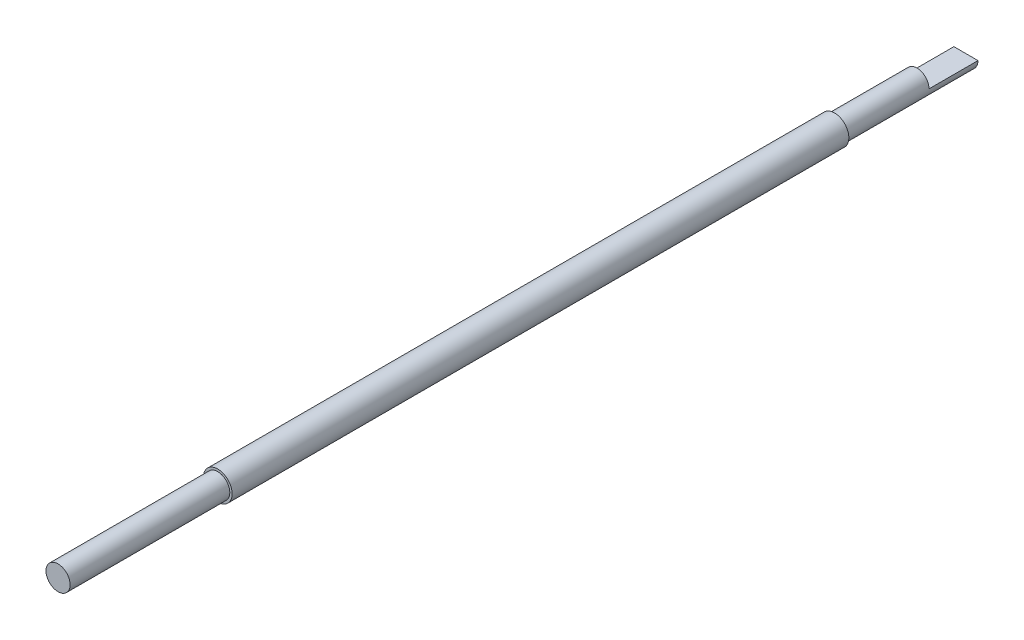
SolidWorks part; units mm, degrees
ref_plane "Front Plane" through (0, 0, 0) normal (0, 0, 1) x (1, 0, 0)
ref_plane "Top Plane" through (0, 0, 0) normal (0, 1, 0) x (1, 0, 0)
ref_plane "Right Plane" through (0, 0, 0) normal (1, 0, 0) x (0, 0, -1)
sketch "Sketch1" plane through (0, 0, 0) normal (0, 0, 1) x (1, 0, 0)
  circle A0 centre (0, 0) radius 4.7625
  dimension "D1" = 9.525
extrude "Boss-Extrude1" add sketch "Sketch1" along normal blind 301.26
sketch "Sketch3" plane through (0, 0, 0) normal (0, 0, -1) x (-1, 0, 0)
  circle A0 centre (0, 0) radius 4.7625
  circle A1 centre (0, 0) radius 4
  dimension "D1" = 9.525
  dimension "D2" = 8
extrude "Cut-Extrude2" cut sketch "Sketch3" against normal blind 43.61
sketch "Sketch4" plane through (0, 0, 0) normal (0, 0, -1) x (-1, 0, 0)
  line L0 (-4, 0) -> (4, 0)
  circle A0 centre (0, 0) radius 4 construction
  circle A1 centre (0, 0) radius 4 construction
  circle A2 centre (0, 0) radius 4
  circle M2 centre (0, 0) radius 4
  dimension "D1" = 8
  dimension "D2" = 8
extrude "Cut-Extrude3" cut sketch "Sketch4" against normal blind 16.26 contours L0 M2
sketch "Sketch5" plane through (0, 0, 301.26) normal (0, 0, 1) x (1, 0, 0)
  circle A0 centre (0, 0) radius 4
  circle A1 centre (0, 0) radius 4.7625
  dimension "D1" = 8
  dimension "D2" = 9.525
extrude "Cut-Extrude4" cut sketch "Sketch5" against normal blind 53
